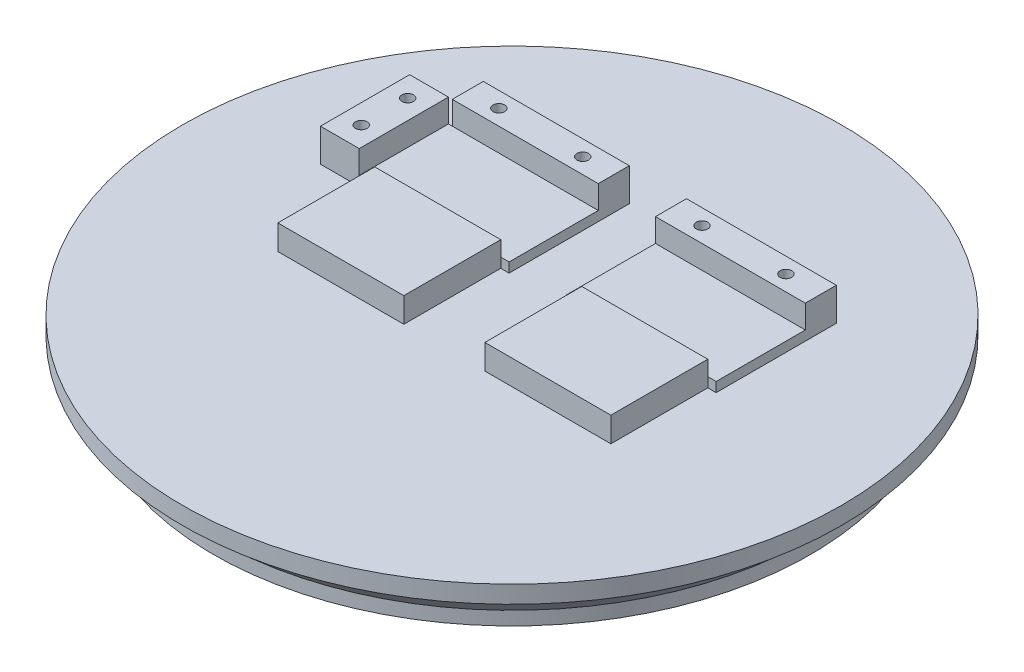
SolidWorks part; units mm, degrees
ref_plane "Front Plane" through (0, 0, 0) normal (0, 0, 1) x (1, 0, 0)
ref_plane "Top Plane" through (0, 0, 0) normal (0, 1, 0) x (1, 0, 0)
ref_plane "Right Plane" through (0, 0, 0) normal (1, 0, 0) x (0, 0, -1)
sketch "Sketch1" plane through (0, 0, 0) normal (0, 0, 1) x (1, 0, 0)
  line L0 (0, 12) -> (0, 15)
  line L1 (0, 15) -> (85, 15)
  line L2 (85, 15) -> (85, 10.5)
  line L3 (85, 10.5) -> (84, 10.5)
  line L4 (77, 3.5) -> (77, 0)
  line L5 (77, 0) -> (71, 0)
  line L6 (71, 0) -> (71, 12)
  line L7 (71, 12) -> (23.75, 12)
  line L8 (84, 10.5) -> (77, 3.5)
  line L9 (0, 12) -> (0, 9)
  line L10 (0, 9) -> (6.5, 9)
  line L11 (6.5, 9) -> (6.5, 6)
  line L12 (6.5, 6) -> (21.25, 6)
  line L13 (21.25, 6) -> (21.25, -7.5)
  line L15 (23.75, -7.5) -> (23.75, 12)
  line L16 (21.25, -7.5) -> (23.75, -7.5)
  point P6 (77, 10.5)
  dimension "D1" = 85
  dimension "D2" = 3
  dimension "D3" = 6
  dimension "D4" = 8
  dimension "D5" = 10.5
  dimension "D6" = 1.5
  dimension "D7" = 21.25
  dimension "D8" = 4.5
  dimension "D10" = 3
  dimension "D11" = 2.5
  dimension "D12" = 13.5
  dimension "D13" = 6.5
  dimension "D14" = 3
  dimension "D15" = 18
  dimension "D16" = 16.5
revolve "Revolve1" add sketch "Sketch1" angle 360 about L9
sketch "Sketch2" plane through (0, 12, 0) normal (0, -1, 0) x (1, 0, 0)
  line L1 (0, 70.2924) -> (-60.875, 35.1462)
  line L2 (-60.875, 35.1462) -> (-60.875, -35.1462)
  line L3 (-60.875, -35.1462) -> (0, -70.2924)
  line L4 (0, -70.2924) -> (60.875, -35.1462)
  line L5 (60.875, -35.1462) -> (60.875, 35.1462)
  line L6 (60.875, 35.1462) -> (0, 70.2924)
  circle A0 centre (0, 0) radius 71 construction
  circle A1 centre (0, 0) radius 71
  circle A2 centre (0, 0) radius 60.875 construction
  circle M8 centre (0, 0) radius 71
  dimension "D1" = 121.75
extrude "Boss-Extrude1" add sketch "Sketch2" along normal blind 11 contours L2 M8 | L1 M8 | L3 M8 | L4 M8 | L5 M8 | L6 M8
sketch "Sketch10" plane through (0, 15, 0) normal (0, 1, 0) x (1, 0, 0)
  line L0 (0, 99.1575) -> (0, -95.7853) construction
  line L1 (-99.194, 0) -> (98.9918, 0) construction
  line L2 (-53.4, 32) -> (-53.4, 9) construction
  line L3 (5, 9) -> (43.65, 9) construction
  line L4 (5, 9) -> (5, 32) construction
  line L5 (5, 32) -> (43.65, 32) construction
  line L6 (43.65, 9) -> (43.65, 32) construction
  line L7 (-48.4, 32) -> (-9.75, 32) construction
  line L8 (-48.4, 32) -> (-48.4, 9) construction
  line L9 (-48.4, 9) -> (-9.75, 9) construction
  line L10 (-9.75, 32) -> (-9.75, 9) construction
  line L11 (-48.4, 32) -> (-58.4, 32)
  line L12 (-48.4, 32) -> (-48.4, 9)
  line L13 (-48.4, 9) -> (-58.4, 9)
  line L14 (-58.4, 32) -> (-58.4, 9)
  line L15 (-48.4, 32) -> (-9.75, 32)
  line L16 (-48.4, 32) -> (-48.4, 40)
  line L17 (-48.4, 40) -> (-9.75, 40)
  line L18 (-9.75, 32) -> (-9.75, 40)
  line L19 (-48.4, 36) -> (-9.75, 36) construction
  line L20 (5, 32) -> (5, 40)
  line L21 (5, 36) -> (43.65, 36) construction
  line L22 (43.65, 32) -> (43.65, 40)
  line L23 (5, 32) -> (43.65, 32)
  line L24 (5, 40) -> (43.65, 40)
  line L25 (5, 32) -> (43.65, 32) construction
  line L26 (48.65, 32) -> (48.65, 9) construction
  line L27 (53.65, 32) -> (53.65, 9) construction
  line L28 (53.65, 32) -> (53.65, 9)
  line L29 (53.65, 32) -> (43.65, 32)
  line L30 (53.65, 9) -> (43.65, 9)
  line L31 (43.65, 32) -> (43.65, 9)
  line L32 (-47.4, 40) -> (-47.4, 32)
  line L33 (42.65, 40) -> (42.65, 32)
  circle A0 centre (-53.4, 26.5) radius 1.5
  circle A1 centre (-53.4, 14.5) radius 1.5
  circle A2 centre (-39.4, 36) radius 1.5
  circle A3 centre (-17.75, 36) radius 1.5
  circle A4 centre (13, 36) radius 1.5
  circle A5 centre (34.65, 36) radius 1.5
  circle A6 centre (48.65, 14.5) radius 1.5
  circle A7 centre (48.65, 26.5) radius 1.5
  dimension "D11" = 3
  dimension "D12" = 5.5
  dimension "D14" = 3
  dimension "D19" = 3
  dimension "D22" = 3
  dimension "D1" = 23
  dimension "D2" = 38.65
  dimension "D3" = 40
  dimension "D4" = 5
  dimension "D5" = 14.75
  dimension "D6" = 23
  dimension "D7" = 38.65
  dimension "D9" = 10
  dimension "D10" = 8
  dimension "D13" = 5.5
  dimension "D15" = 8
  dimension "D16" = 8
  dimension "D17" = 8
  dimension "D18" = 8
  dimension "D20" = 10
  dimension "D21" = 5.5
  dimension "D23" = 5.5
  dimension "D24" = 1
  dimension "D25" = 1
extrude "Boss-Extrude6" add sketch "Sketch10" along normal blind 8.5 contours L17 L32 L15 L18 A3 A2 | L11 L14 L13 L12 A1 A0 | L33 L24 L20 L23 A5 A4 | L24 L33 L23 L22
sketch "Sketch11" plane through (0, 15, 0) normal (0, 1, 0) x (1, 0, 0)
  line L0 (-48.4, 9) -> (-58.4, 9) construction
  line L1 (-48.4, 32) -> (-9.75, 32)
  line L2 (-48.4, 32) -> (-48.4, 9)
  line L3 (-48.4, 9) -> (-9.75, 9)
  line L4 (-9.75, 32) -> (-9.75, 9)
  line L5 (-9.75, 32) -> (-9.75, 40) construction
  line L6 (5, 32) -> (5, 40) construction
  line L7 (43.65, 32) -> (5, 32)
  line L8 (43.65, 32) -> (43.65, 9)
  line L9 (43.65, 9) -> (5, 9)
  line L10 (5, 32) -> (5, 9)
  line L12 (43.65, 32) -> (43.65, 40) construction
sketch "Sketch12" plane through (0, 12, 0) normal (0, -1, 0) x (1, 0, 0)
  circle A0 centre (0, 0) radius 57.5
  circle A1 centre (0, 0) radius 23.75 construction
  circle A2 centre (0, 0) radius 23.75
  dimension "D1" = 115
extrude "Cut-Extrude8" cut sketch "Sketch12" against normal blind 1
extrude "Boss-Extrude7" add sketch "Sketch11" along normal blind 2.5
sketch "Sketch14" plane through (0, 15, 0) normal (0, 1, 0) x (1, 0, 0)
  line L0 (43.65, 9) -> (43.65, 32) construction
  line L1 (43.65, 32) -> (5, 32) construction
  line L2 (5, 32) -> (5, 9) construction
  line L3 (5, 9) -> (43.65, 9) construction
  line L4 (-48.4, 32) -> (-48.4, 9) construction
  line L5 (-48.4, 9) -> (-9.75, 9) construction
  line L6 (-9.75, 9) -> (-9.75, 32) construction
  line L7 (-9.75, 32) -> (-47.4, 32) construction
  line L8 (-47.4, 32) -> (-48.4, 32) construction
  line L9 (43.65, 9) -> (43.65, 32)
  line L10 (43.65, 32) -> (5, 32)
  line L11 (5, 32) -> (5, 9)
  line L12 (5, 9) -> (43.65, 9)
  line L13 (-48.4, 32) -> (-48.4, 9)
  line L14 (-48.4, 9) -> (-9.75, 9)
  line L15 (-9.75, 9) -> (-9.75, 32)
  line L16 (-9.75, 32) -> (-47.4, 32)
  line L17 (-47.4, 32) -> (-48.4, 32)
  line L23 (-44.4, 9) -> (-11.9, 9)
  line L24 (-44.4, 9) -> (-44.4, -16)
  line L25 (-44.4, -16) -> (-11.9, -16)
  line L26 (-11.9, 9) -> (-11.9, -16)
  line L27 (9, 9) -> (41.5, 9)
  line L28 (9, 9) -> (9, -16)
  line L29 (9, -16) -> (41.5, -16)
  line L30 (41.5, 9) -> (41.5, -16)
  dimension "D1" = 32.5
  dimension "D2" = 32.5
  dimension "D3" = 2.15
  dimension "D4" = 2.15
  dimension "D5" = 25
extrude "Boss-Extrude8" add sketch "Sketch14" along normal blind 6.4 contours L26 L14 L24 L25 | L30 L12 L28 L29
